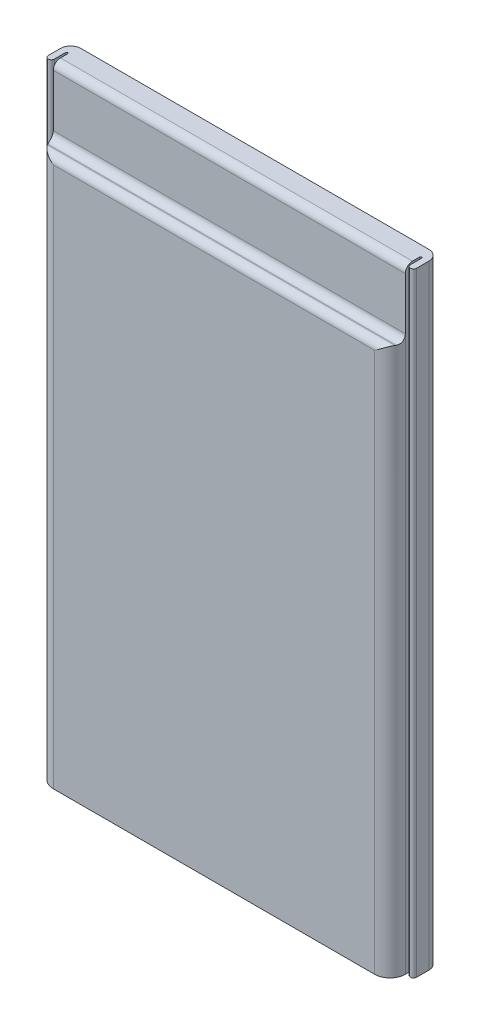
SolidWorks part; units mm, degrees
ref_plane "Front" through (0, 0, 0) normal (0, 0, 1) x (1, 0, 0)
ref_plane "Top" through (0, 0, 0) normal (0, 1, 0) x (1, 0, 0)
ref_plane "Right" through (0, 0, 0) normal (1, 0, 0) x (0, 0, -1)
sketch "Эскиз1" plane through (0, 0, 0) normal (0, 1, 0) x (1, 0, 0)
  line L0 (-17, 0) -> (17, 0)
  line L1 (-15.7, -4) -> (15.7, -4)
  line L2 (-18, -1) -> (-18, -2.2)
  line L3 (18, -1) -> (18, -2.2)
  line L4 (-17.2, -2.5) -> (-17.2, -1.1)
  line L5 (17.2, -1.1) -> (17.2, -2.5)
  line L6 (17.4, -2.2) -> (17.4, -1.1)
  line L7 (-17.4, -2.2) -> (-17.4, -1.1)
  arc A0 (-17, 0) -> (-18, -1) centre (-17, -1) ccw
  arc A1 (17, 0) -> (18, -1) centre (17, -1) cw
  arc A2 (-17.2, -2.5) -> (-15.7, -4) centre (-15.7, -2.5) ccw
  arc A3 (17.2, -2.5) -> (15.7, -4) centre (15.7, -2.5) cw
  arc A4 (18, -2.2) -> (17.4, -2.2) centre (17.7, -2.2) cw
  arc A5 (17.2, -1.1) -> (17.4, -1.1) centre (17.3, -1.1) cw
  arc A6 (-18, -2.2) -> (-17.4, -2.2) centre (-17.7, -2.2) ccw
  arc A7 (-17.2, -1.1) -> (-17.4, -1.1) centre (-17.3, -1.1) ccw
  point P20 (17.3, -1)
  point P21 (17.7, -2.5)
  point P27 (-17.3, -1)
  point P28 (-17.7, -2.5)
  dimension "D1" = 36
  dimension "D3" = 1.5
  dimension "D4" = 1
  dimension "D5" = 0.3
  dimension "D6" = 0.1
  dimension "D2" = 4
extrude "Бобышка-Вытянуть1" add sketch "Эскиз1" along normal mid plane 60
sketch "Эскиз2" plane through (0, 0, 0) normal (1, 0, 0) x (0, 0, -1)
  line L0 (-2.5, 29.3) -> (-2.5, 24.2)
  line L1 (-3.2, 23.5) -> (-3.3, 23.5)
  line L2 (-4, 30) -> (-4, 22.8)
  line L3 (-4, 30) -> (-4, -30) construction
  line L6 (-4, 30) -> (-1.8, 30)
  line L7 (0, 30) -> (-1, 30) construction
  arc A0 (-2.5, 24.2) -> (-3.2, 23.5) centre (-3.2, 24.2) cw
  arc A1 (-3.3, 23.5) -> (-4, 22.8) centre (-3.3, 22.8) ccw
  arc A2 (-1.8, 30) -> (-2.5, 29.3) centre (-1.8, 29.3) ccw
  point P15 (-1.7689, 24.5)
  dimension "D1" = 0.7
  dimension "D2" = 2.5
  dimension "D3" = 6.5
extrude "Вырез-Вытянуть1" cut sketch "Эскиз2" against normal up to next and the other way up to next
